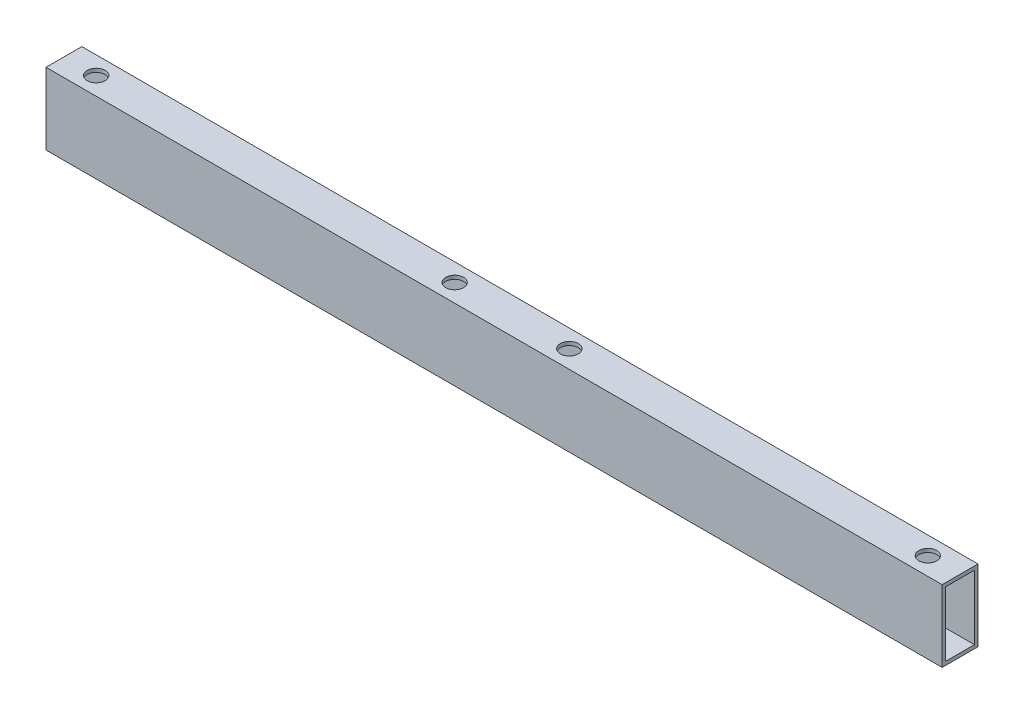
SolidWorks part; units mm, degrees
ref_plane "Front Plane" through (0, 0, 0) normal (0, 0, 1) x (1, 0, 0)
ref_plane "Top Plane" through (0, 0, 0) normal (0, 1, 0) x (1, 0, 0)
ref_plane "Right Plane" through (0, 0, 0) normal (1, 0, 0) x (0, 0, -1)
sketch "Sketch1" plane through (0, 0, 0) normal (1, 0, 0) x (0, 0, -1)
  line L0 (-4, -9) -> (-4, 9)
  line L1 (-5, -10) -> (5, -10)
  line L2 (-5, -10) -> (-5, 10)
  line L3 (-5, 10) -> (5, 10)
  line L4 (5, -10) -> (5, 10)
  line L5 (-5, -10) -> (5, 10) construction
  line L6 (-5, 10) -> (5, -10) construction
  line L7 (-4, 9) -> (4, 9)
  line L8 (4, -9) -> (4, 9)
  line L9 (-4, -9) -> (4, -9)
  point P0 (0, 0)
  dimension "D1" = 10
  dimension "D2" = 20
  dimension "D3" = 1
extrude "Boss-Extrude1" add sketch "Sketch1" along normal blind 250
sketch "Sketch2" plane through (0, 10, 0) normal (0, 1, 0) x (1, 0, 0)
  line L2 (250, 5) -> (250, -5) construction
  line L3 (0, 5) -> (0, -5) construction
  circle A1 centre (241, 0) radius 2.5
  circle A2 centre (9, 0) radius 2.5
  dimension "D2" = 5
  dimension "D6" = 5
  dimension "D3" = 9
  dimension "D5" = 9
extrude "Cut-Extrude1" cut sketch "Sketch2" against normal blind 20
sketch "Sketch3" plane through (0, 10, 0) normal (0, 1, 0) x (1, 0, 0)
  line L0 (125, 5) -> (125, -5) construction
  line L1 (250, 5) -> (0, 5) construction
  line L2 (250, -5) -> (0, -5) construction
  circle A0 centre (109, 0) radius 2.5
  circle A1 centre (141, 0) radius 2.5
  dimension "D5" = 5
  dimension "D6" = 5
  dimension "D3" = 32
  dimension "D4" = 16
extrude "Cut-Extrude2" cut sketch "Sketch3" against normal blind 20
